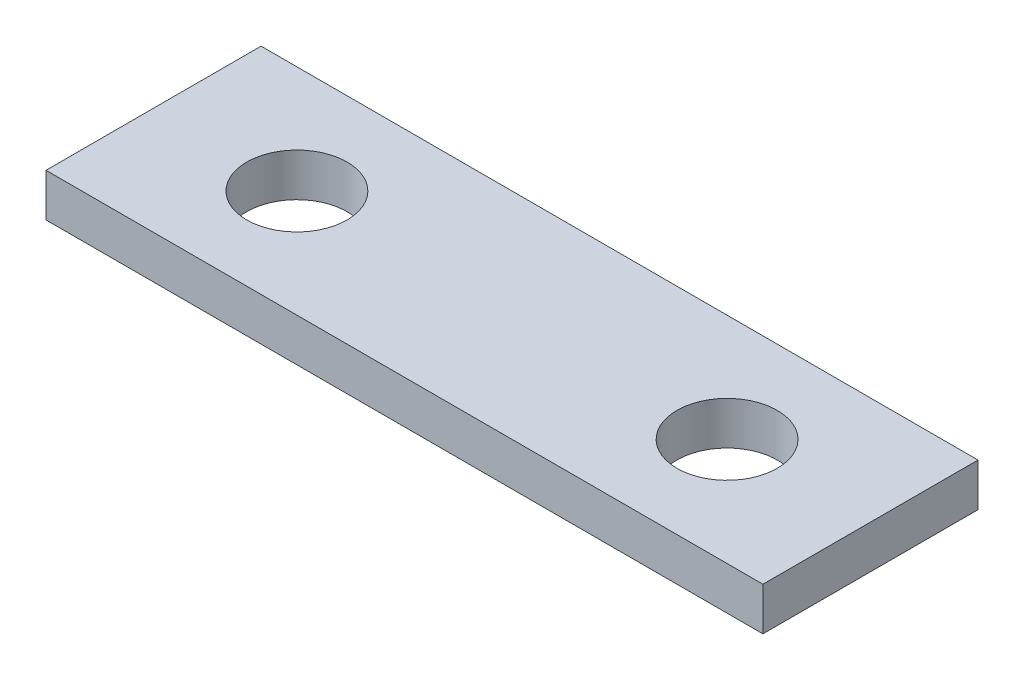
SolidWorks part; units mm, degrees
ref_plane "前视基准面" through (0, 0, 0) normal (0, 0, 1) x (1, 0, 0)
ref_plane "上视基准面" through (0, 0, 0) normal (0, 1, 0) x (1, 0, 0)
ref_plane "右视基准面" through (0, 0, 0) normal (1, 0, 0) x (0, 0, -1)
sketch "草图1" plane through (0, 0, 0) normal (0, 1, 0) x (1, 0, 0)
  line L0 (-1000, 15) -> (49000, 15) construction
  line L1 (0, 0) -> (100, 0)
  line L2 (0, 0) -> (0, 30)
  line L3 (0, 30) -> (100, 30)
  line L4 (100, 0) -> (100, 30)
  line L5 (50, -1000) -> (50, 49000) construction
  circle A0 centre (20, 15) radius 7
  circle A1 centre (80, 15) radius 7
  point P8 (0, 15)
  point P15 (50, 0)
  dimension "D3" = 14
  dimension "D4" = 14
  dimension "D1" = 100
  dimension "D2" = 30
  dimension "D5" = 60
extrude "凸台-拉伸1" add sketch "草图1" along normal blind 6
